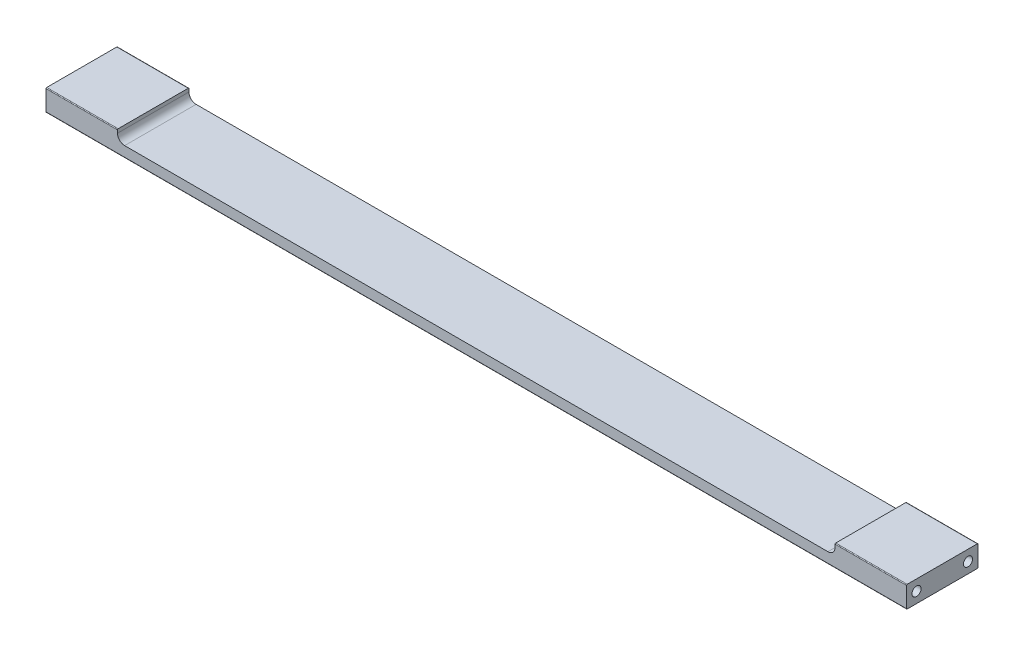
SolidWorks part; units mm, degrees
material "6061 Alloy"
ref_plane "Front Plane" through (0, 0, 0) normal (0, 0, 1) x (1, 0, 0)
ref_plane "Top Plane" through (0, 0, 0) normal (0, 1, 0) x (1, 0, 0)
ref_plane "Right Plane" through (0, 0, 0) normal (1, 0, 0) x (0, 0, -1)
sketch "Sketch1" plane through (0, 0, 0) normal (0, 1, 0) x (1, 0, 0)
  line L1 (191.135, -15.875) -> (-191.135, -15.875)
  line L2 (191.135, -15.875) -> (191.135, 15.875)
  line L3 (191.135, 15.875) -> (-191.135, 15.875)
  line L4 (-191.135, -15.875) -> (-191.135, 15.875)
  line L5 (191.135, -15.875) -> (-191.135, 15.875) construction
  line L6 (191.135, 15.875) -> (-191.135, -15.875) construction
  point P0 (0, 0)
  dimension "Length" = 382.27
  dimension "Width" = 31.75
sketch "Sketch2" plane through (0, 0, 0) normal (1, 0, 0) x (0, 0, -1)
  line L0 (15.875, 4.7625) -> (15.875, -4.7625) construction
  point P2 (15.875, 0)
  dimension "Thickness" = 9.525
sketch "Sketch3" plane through (0, 0, 0) normal (0, 1, 0) x (1, 0, 0)
  line L1 (-191.135, 15.875) -> (191.135, 15.875)
  line L2 (-191.135, 15.875) -> (-191.135, -15.875)
  line L3 (-191.135, -15.875) -> (191.135, -15.875)
  line L4 (191.135, 15.875) -> (191.135, -15.875)
extrude "Boss-Extrude1" add sketch "Sketch3" against normal up to vertex (4.7625 mm away) and the other way up to vertex (4.7625 mm away) up to point (0, -4.7625, -15.875) other way up to point (0, 4.7625, -15.875)
fillet "Fillet1" radius 0.3143 4 edges at (0, -4.7625, 15.875) (0, -4.7625, -15.875) (0, 4.7625, -15.875) (0, 4.7625, 15.875)
sketch "Sketch4" plane through (-191.135, 0, 0) normal (-1, 0, 0) x (0, 0, 1)
  line L0 (0, 0) -> (11.43, 0) construction
  line L1 (0, 0) -> (-11.43, 0) construction
  line L2 (0, 0) -> (0, 2.7298) construction
  dimension "D1" = 11.43
  dimension "D2" = 11.43
hole_wizard "Tap Drill for #10-32 Tap1" positions "Sketch5" profile "Sketch6" hole size "#10-32" standard "ANSI Inch"
sketch "Sketch5" plane through (-191.135, 0, 0) normal (-1, 0, 0) x (0, 0, 1)
  point P0 (-11.43, 0)
  point P3 (11.43, 0)
sketch "Sketch6" plane through (-191.135, 0, -11.43) normal (0, 1, 0) x (0, 0, 1)
  line L0 (0, 0) -> (0, 26.6133)
  line L1 (0, 26.6133) -> (2.0193, 25.4)
  line L2 (2.0193, 25.4) -> (2.0193, 0)
  line L5 (2.0193, 0) -> (0, 0)
  line L10 (0, 26.6133) -> (-2.0193, 25.4) construction
  line L11 (0, -6.35) -> (0, 107.95) construction
  dimension "Hole Dia." = 4.0386
  dimension "Hole Depth" = 25.4
  dimension "Drill Angle" = 118
hole_wizard "Tap Drill for #10-32 Tap2" positions "Sketch7" profile "Sketch8" hole size "#10-32" standard "ANSI Inch"
sketch "Sketch7" plane through (191.135, 0, 0) normal (1, 0, 0) x (0, 0, -1)
  point P0 (-11.43, 0)
  point P3 (11.43, 0)
sketch "Sketch8" plane through (191.135, 0, 11.43) normal (0, 1, 0) x (0, 0, -1)
  line L0 (0, 0) -> (0, 26.6133)
  line L1 (0, 26.6133) -> (2.0193, 25.4)
  line L2 (2.0193, 25.4) -> (2.0193, 0)
  line L5 (2.0193, 0) -> (0, 0)
  line L10 (0, 26.6133) -> (-2.0193, 25.4) construction
  line L11 (0, -6.35) -> (0, 107.95) construction
  dimension "Hole Dia." = 4.0386
  dimension "Hole Depth" = 25.4
  dimension "Drill Angle" = 118
sketch "Sketch9" plane through (0, 0, -15.875) normal (0, 0, -1) x (-1, 0, 0)
  line L0 (159.385, 4.7625) -> (159.385, 3.175)
  line L7 (-191.135, 4.7625) -> (191.135, 4.7625) construction
  line L8 (156.21, 0) -> (-156.21, 0)
  line L9 (-159.385, 3.175) -> (-159.385, 4.7625)
  line L10 (-159.385, 4.7625) -> (159.385, 4.7625)
  line L11 (191.135, 113.2576) -> (191.135, 39.0958) construction
  line L12 (-191.135, 113.2576) -> (-191.135, 39.0958) construction
  arc A0 (159.385, 3.175) -> (156.21, 0) centre (156.21, 3.175) cw
  arc A1 (-156.21, 0) -> (-159.385, 3.175) centre (-156.21, 3.175) cw
  point P15 (159.385, 0)
  point P18 (-159.385, 0)
  dimension "D4" = 3.175
  dimension "D1" = 31.75
  dimension "D2" = 31.75
  dimension "D3" = 4.7625
extrude "Cut-Extrude1" cut sketch "Sketch9" against normal through all
equation "\"D1@Fillet1\" = \"Thickness@Sketch2\" * .033"
